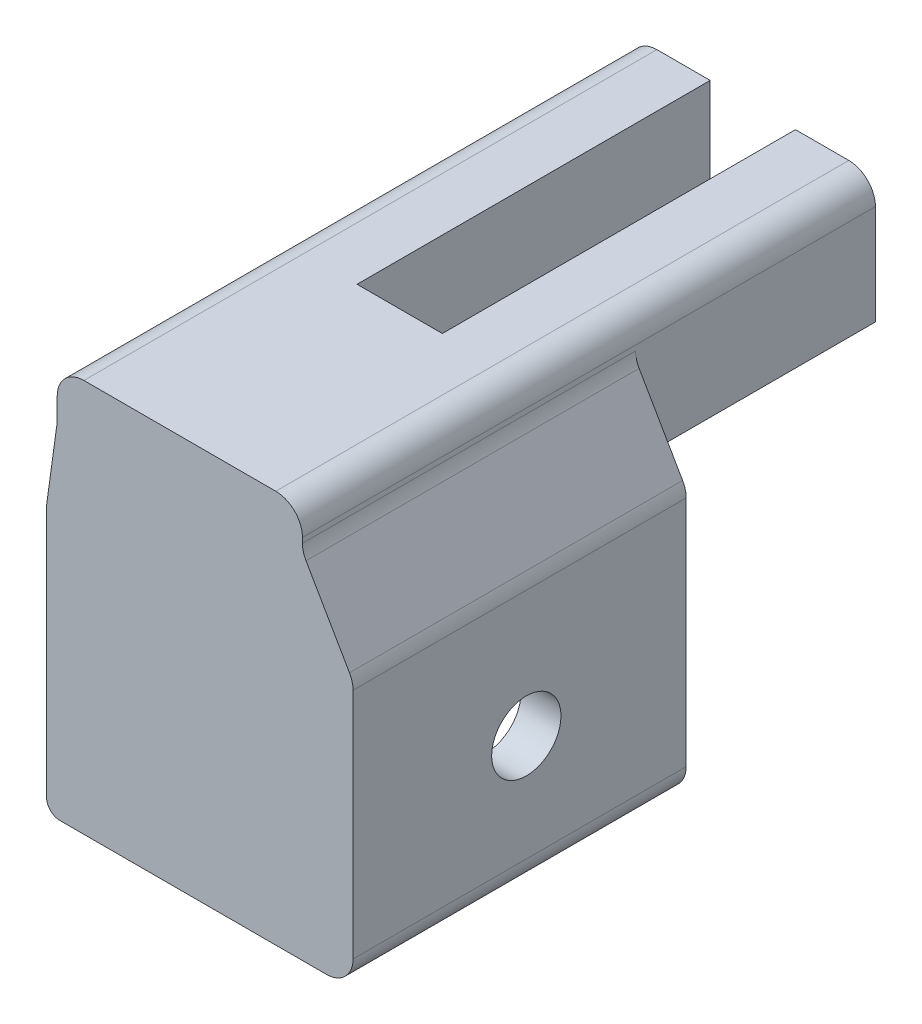
SolidWorks part; units mm, degrees
ref_plane "正面" through (0, 0, 0) normal (0, 0, 1) x (1, 0, 0)
ref_plane "平面" through (0, 0, 0) normal (0, 1, 0) x (1, 0, 0)
ref_plane "右側面" through (0, 0, 0) normal (1, 0, 0) x (0, 0, -1)
sketch "ｽｹｯﾁ1" plane through (0, 0, 0) normal (0, 0, 1) x (1, 0, 0)
  line L1 (-10, 10) -> (10, 10)
  line L2 (-10, 10) -> (-10, -10)
  line L3 (-10, -10) -> (10, -10)
  line L4 (10, 10) -> (10, -10)
  line L5 (-10, 10) -> (10, -10) construction
  line L6 (-10, -10) -> (10, 10) construction
  point P0 (0, 0)
  dimension "D1" = 20
extrude "ﾎﾞｽ - 押し出し1" add sketch "ｽｹｯﾁ1" along normal blind 3
sketch "ｽｹｯﾁ2" plane through (0, 0, 0) normal (0, 0, -1) x (-1, 0, 0)
  line L0 (-10, 10) -> (10, 10) construction
  line L1 (-3.5, 4) -> (3.5, 4)
  line L2 (-3.5, 4) -> (-3.5, 10)
  line L3 (-3.5, 10) -> (3.5, 10)
  line L4 (3.5, 4) -> (3.5, 10)
  line L5 (-3.5, 4) -> (3.5, 10) construction
  line L6 (-3.5, 10) -> (3.5, 4) construction
  line L7 (0, 0) -> (0, 7) construction
  point P0 (0, 7)
  dimension "D1" = 6
  dimension "D2" = 7
extrude "ﾎﾞｽ - 押し出し2" add sketch "ｽｹｯﾁ2" along normal blind 40
sketch "ｽｹｯﾁ3" plane through (0, 0, 3) normal (0, 0, 1) x (1, 0, 0)
  line L0 (-10, -10) -> (10, -10) construction
  line L1 (10, 10) -> (13, 10)
  line L2 (10, 10) -> (10, -10)
  line L3 (10, -10) -> (13, -10)
  line L4 (13, 10) -> (13, -10)
  dimension "D1" = 3
extrude "ﾎﾞｽ - 押し出し3" add sketch "ｽｹｯﾁ3" against normal blind 25
sketch "ｽｹｯﾁ4" plane through (13, 0, 0) normal (1, 0, 0) x (0, 0, -1)
  line L0 (0, 0) -> (22, 0) construction
  line L1 (22, -10) -> (22, 10) construction
  circle A0 centre (10, 0) radius 2.6
  dimension "D1" = 10
  dimension "D2" = 5.2
extrude "ｶｯﾄ - 押し出し1" cut sketch "ｽｹｯﾁ4" against normal up to next
fillet "ﾌｨﾚｯﾄ1" radius 1 1 edges at (-10, -10, 1.5)
ref_plane "平面1" through (0, 0, -13.5) normal (0, 0, -1) x (-1, 0, 0)
sketch "ｽｹｯﾁ5" plane through (0, 0, -13.5) normal (0, 0, -1) x (-1, 0, 0)
  line L0 (3.5, 10) -> (-3.5, 10) construction
  line L1 (-1.6, 6.1) -> (1.6, 6.1)
  line L2 (-1.6, 6.1) -> (-1.6, 10)
  line L3 (-1.6, 10) -> (1.6, 10)
  line L4 (1.6, 6.1) -> (1.6, 10)
  line L5 (-1.6, 6.1) -> (1.6, 10) construction
  line L6 (-1.6, 10) -> (1.6, 6.1) construction
  line L7 (0, 8.05) -> (0, 0) construction
  point P0 (0, 8.05)
  dimension "D1" = 3.2
  dimension "D2" = 3.9
extrude "ｶｯﾄ - 押し出し2" cut sketch "ｽｹｯﾁ5" along normal blind 30
sketch "ｽｹｯﾁ6" plane through (0, 0, 3) normal (0, 0, 1) x (1, 0, 0)
  line L0 (13, 10) -> (-10, 10) construction
  line L1 (3.2, 10) -> (9.2, 10)
  line L2 (3.2, 10) -> (3.2, 19.5)
  line L3 (3.2, 19.5) -> (9.2, 19.5)
  line L4 (9.2, 10) -> (9.2, 19.5)
  line L5 (0, 0) -> (0, 10) construction
  line L6 (-3.2, 19.5) -> (-9.2, 19.5)
  line L7 (-9.2, 10) -> (-9.2, 19.5)
  line L8 (-3.2, 10) -> (-9.2, 10)
  line L9 (-3.2, 10) -> (-3.2, 19.5)
  dimension "D1" = 6.4
  dimension "D2" = 9.5
  dimension "D3" = 6
extrude "ﾎﾞｽ - 押し出し4" add sketch "ｽｹｯﾁ6" against normal up to surface (43 mm away) up to face at (0, 7.525, -40)
chamfer "面取り1" distance 0.5 angle 45 2 edges at (-3.5, 10, -20) (3.5, 10, -20)
sketch "ｽｹｯﾁ7" plane through (0, 0, 3) normal (0, 0, 1) x (1, 0, 0)
  line L1 (-3.2, 19.5) -> (3.2, 19.5)
  line L2 (-3.2, 19.5) -> (-3.2, 10)
  line L3 (-3.2, 10) -> (3.2, 10)
  line L4 (3.2, 19.5) -> (3.2, 10)
extrude "ﾎﾞｽ - 押し出し5" add sketch "ｽｹｯﾁ7" against normal blind 16.5
sketch "ｽｹｯﾁ8" plane through (0, 0, 3) normal (0, 0, 1) x (1, 0, 0)
  line L0 (13, 10) -> (9.2, 16.5818)
  line L1 (9.2, 10) -> (9.2, 19.5) construction
  line L2 (9.2, 16.5818) -> (9.2, 10)
  line L3 (9.2, 10) -> (13, 10)
  dimension "D1" = 60
extrude "ﾎﾞｽ - 押し出し6" add sketch "ｽｹｯﾁ8" against normal up to surface (25 mm away) up to face at (11.5, 0, -22)
fillet "ﾌｨﾚｯﾄ2" radius 2 5 edges at (13, -10, -9.5) (13, 10, -9.5) (9.2, 16.5818, -9.5) (9.2, 19.5, -18.5) (-9.2, 19.5, -18.5)
sketch "ｽｹｯﾁ9" plane through (0, 0, 3) normal (0, 0, 1) x (1, 0, 0)
  line L0 (-10, 10) -> (-9.2, 15.8)
  line L1 (-9.2, 17.5) -> (-9.2, 10) construction
  line L2 (-9.2, 15.8) -> (-9.2, 10)
  line L3 (-9.2, 10) -> (-10, 10)
  dimension "D1" = 5.8
extrude "ﾎﾞｽ - 押し出し7" add sketch "ｽｹｯﾁ9" against normal up to surface (43 mm away) up to face at (0, 11.6514, -40)
sketch "ｽｹｯﾁ10" plane through (0, 0, -40) normal (0, 0, -1) x (-1, 0, 0)
  line L0 (3.5, 4) -> (3.5, 9.5) construction
  line L1 (1.6, 6.1) -> (3.5, 6.1)
  line L2 (1.6, 6.1) -> (1.6, 8.1)
  line L3 (1.6, 8.1) -> (3.5, 8.1)
  line L4 (3.5, 6.1) -> (3.5, 8.1)
  dimension "D1" = 2
extrude "ｶｯﾄ - 押し出し3" cut sketch "ｽｹｯﾁ10" against normal up to surface (26.5 mm away) up to face at (0, 11.4, -13.5)
fillet "ﾌｨﾚｯﾄ3" radius 0.5 2 edges at (-3.5, 8.1, -26.75) (-3.5, 6.1, -26.75)
fillet "ﾌｨﾚｯﾄ4" radius 1 2 edges at (3.5, 4, -20) (-3.5, 4, -20)
